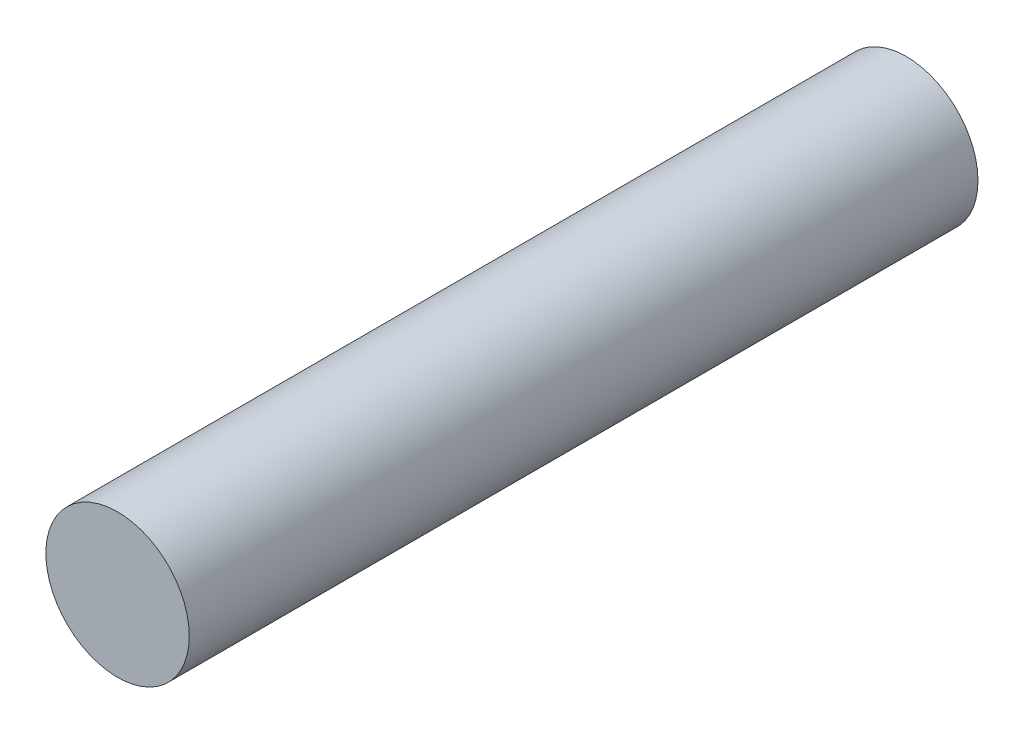
SolidWorks part; units mm, degrees
ref_plane "Front Plane" through (0, 0, 0) normal (0, 0, 1) x (1, 0, 0)
ref_plane "Top Plane" through (0, 0, 0) normal (0, 1, 0) x (1, 0, 0)
ref_plane "Right Plane" through (0, 0, 0) normal (1, 0, 0) x (0, 0, -1)
sketch "Sketch1" plane through (0, 0, 0) normal (0, 0, 1) x (1, 0, 0)
  circle A0 centre (0, 0) radius 10
extrude "Boss-Extrude1" add sketch "Sketch1" along normal blind 110
